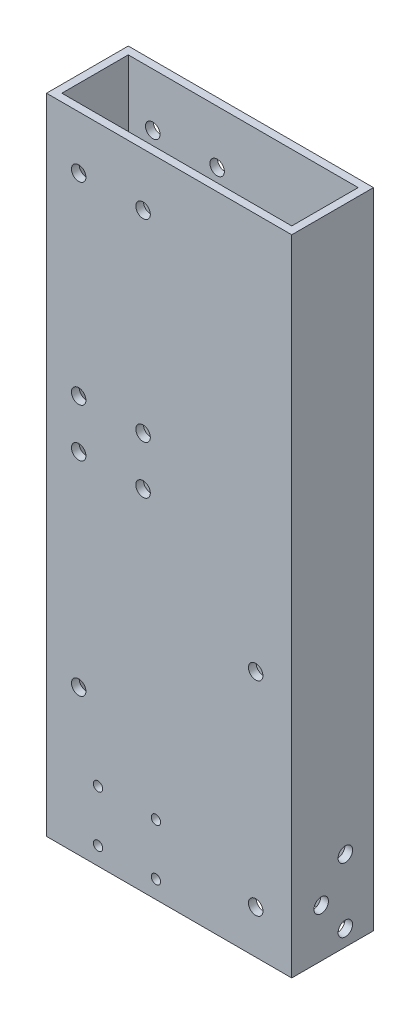
SolidWorks part; units mm, degrees
material "6061-T6 (SS)"
ref_plane "Front Plane" through (0, 0, 0) normal (0, 0, 1) x (1, 0, 0)
ref_plane "Top Plane" through (0, 0, 0) normal (0, 1, 0) x (1, 0, 0)
ref_plane "Right Plane" through (0, 0, 0) normal (1, 0, 0) x (0, 0, -1)
sketch "Sketch1" plane through (0, 0, 0) normal (0, 1, 0) x (1, 0, 0)
  line L1 (-76.2, 25.4) -> (76.2, 25.4)
  line L2 (-76.2, 25.4) -> (-76.2, -25.4)
  line L3 (-76.2, -25.4) -> (76.2, -25.4)
  line L4 (76.2, 25.4) -> (76.2, -25.4)
  line L5 (-76.2, 25.4) -> (76.2, -25.4) construction
  line L6 (-76.2, -25.4) -> (76.2, 25.4) construction
  point P0 (0, 0)
  dimension "D1" = 152.4
  dimension "D2" = 50.8
extrude "Extrude-Thin1" add sketch "Sketch1" along normal blind 400 thin
hole_wizard "M8 Clearance Hole1" positions "Sketch3" profile "Sketch4" hole size "M8" standard "ANSI Metric" end condition through all
sketch "Sketch3" plane through (0, 0, 25.4) normal (0, 0, 1) x (1, 0, 0)
  line L0 (-76.2, 227) -> (3.8, 227)
  line L1 (-76.2, 400) -> (-76.2, 0) construction
  line L3 (-76.2, 0) -> (76.2, 0) construction
  line L4 (3.8, 227) -> (3.8, 387)
  line L5 (3.8, 387) -> (-76.2, 387)
  line L6 (-76.2, 387) -> (-76.2, 227)
  line L8 (-56.2, 217) -> (-16.2, 217)
  line L11 (-56.2, 217) -> (-56.2, 153.6667)
  line L12 (-56.2, 153.6667) -> (-56.2, 90.3333)
  line L13 (-56.2, 90.3333) -> (-56.2, 27)
  line L15 (-36.2, 217) -> (-36.2, 227)
  line L17 (-56.2, 27) -> (53.8, 27)
  line L18 (53.8, 27) -> (53.8, 153.6667)
  line L19 (53.8, 153.6667) -> (-56.2, 153.6667)
  line L22 (-56.2, 90.3333) -> (-76.2, 90.3333)
  line L27 (-36.2, 425) -> (-36.2, 387)
  circle A0 centre (-36.2, 425) radius 49.2125
  point P18 (-56.2, 217)
  point P19 (-16.2, 217)
  point P26 (-56.2, 90.3333)
  point P35 (53.8, 27)
  point P36 (53.8, 153.6667)
  dimension "D9" = 98.425
  dimension "D1" = 200
  dimension "D2" = 80
  dimension "D3" = 160
  dimension "D4" = 27
  dimension "D5" = 10
  dimension "D6" = 40
  dimension "D7" = 110
  dimension "D8" = 38
sketch "Sketch4" plane through (53.8, 153.6667, 25.4) normal (1, 0, 0) x (0, -1, 0)
  line L0 (0, 0) -> (0, 50.8)
  line L1 (0, 50.8) -> (4.5, 50.8)
  line L2 (4.5, 50.8) -> (4.5, 0)
  line L5 (4.5, 0) -> (0, 0)
  line L11 (0, -6.35) -> (0, 107.95) construction
  dimension "Thru Hole Dia." = 9
  dimension "Thru Hole Depth" = 50.8
hole_wizard "M8 Clearance Hole2" positions "Sketch5" profile "Sketch6" hole size "M8" standard "ANSI Metric" end condition through all
sketch "Sketch5" plane through (0, 0, 25.4) normal (0, 0, 1) x (1, 0, 0)
  line L1 (-56.2, 367) -> (-16.2, 367)
  line L2 (-56.2, 367) -> (-56.2, 247)
  line L3 (-56.2, 247) -> (-16.2, 247)
  line L4 (-16.2, 367) -> (-16.2, 247)
  line L5 (-56.2, 217) -> (-16.2, 217) construction
  line L6 (-36.2, 227) -> (-36.2, 247)
  line L7 (-76.2, 227) -> (3.8, 227) construction
  point P1 (-56.2, 367)
  point P2 (-16.2, 247)
  point P153 (-56.2, 247)
  point P154 (-16.2, 367)
  dimension "D1" = 20
  dimension "D2" = 120
sketch "Sketch6" plane through (-56.2, 367, 25.4) normal (1, 0, 0) x (0, -1, 0)
  line L0 (0, 0) -> (0, 50.8)
  line L1 (0, 50.8) -> (4.5, 50.8)
  line L2 (4.5, 50.8) -> (4.5, 0)
  line L5 (4.5, 0) -> (0, 0)
  line L11 (0, -6.35) -> (0, 107.95) construction
  dimension "Thru Hole Dia." = 9
  dimension "Thru Hole Depth" = 50.8
hole_wizard "M5 Clearance Hole1" positions "Sketch10" profile "Sketch11" hole size "M5" standard "ANSI Metric" end condition through all
sketch "Sketch10" plane through (0, 0, 25.4) normal (0, 0, 1) x (1, 0, 0)
  line L1 (-8.2, 43) -> (-44.2, 43)
  line L2 (-8.2, 43) -> (-8.2, 11)
  line L3 (-8.2, 11) -> (-44.2, 11)
  line L4 (-44.2, 43) -> (-44.2, 11)
  line L5 (-8.2, 43) -> (-44.2, 11) construction
  line L6 (-8.2, 11) -> (-44.2, 43) construction
  line L8 (-56.2, 27) -> (53.8, 27) construction
  line L9 (-76.2, 400) -> (-76.2, 0) construction
  point P2 (-44.2, 11)
  point P107 (-8.2, 43)
  point P108 (-8.2, 11)
  point P109 (-44.2, 43)
  point P114 (-26.2, 27)
  dimension "D1" = 36
  dimension "D2" = 32
  dimension "D3" = 50
sketch "Sketch11" plane through (-44.2, 11, 25.4) normal (1, 0, 0) x (0, -1, 0)
  line L0 (0, 0) -> (0, 50.8)
  line L1 (0, 50.8) -> (2.9, 50.8)
  line L2 (2.9, 50.8) -> (2.9, 0)
  line L5 (2.9, 0) -> (0, 0)
  line L11 (0, -6.35) -> (0, 107.95) construction
  dimension "Thru Hole Dia." = 5.8
  dimension "Thru Hole Depth" = 50.8
hole_wizard "M8 Clearance Hole3" positions "Sketch12" profile "Sketch14" hole size "M8" standard "ANSI Metric"
sketch "Sketch12" plane through (76.2, 0, 0) normal (1, 0, 0) x (0, 0, -1)
  line L1 (-7.9, 50) -> (7.1, 50)
  line L2 (-7.9, 50) -> (-7.9, 10)
  line L3 (-7.9, 10) -> (7.1, 10)
  line L4 (7.1, 50) -> (7.1, 10)
  line L5 (-25.4, 0) -> (25.4, 0) construction
  line L6 (-25.4, 90.3333) -> (-25.4, 27) construction
  point P1 (-7.9, 50)
  point P87 (-7.9, 10)
  point P98 (7.1, 30)
  dimension "D1" = 10
  dimension "D2" = 17.5
  dimension "D3" = 15
  dimension "D4" = 40
sketch "Sketch14" plane through (76.2, 50, 7.9) normal (0, 1, 0) x (0, 0, -1)
  line L0 (0, 0) -> (0, 4.7625)
  line L1 (0, 4.7625) -> (4.5, 4.7625)
  line L2 (4.5, 4.7625) -> (4.5, 0)
  line L5 (4.5, 0) -> (0, 0)
  line L11 (0, -6.35) -> (0, 107.95) construction
  dimension "Thru Hole Dia." = 9
  dimension "Thru Hole Depth" = 4.7625
hole_wizard "Ø20.0 (20) Diameter Hole1" positions "Sketch15" profile "Sketch16" hole size "Ø20.0" standard "ANSI Metric"
sketch "Sketch15" plane through (-76.2, 0, 0) normal (-1, 0, 0) x (0, 0, 1)
  line L0 (7.9, 50) -> (-7.1, 30)
  point P0 (0.4, 40)
sketch "Sketch16" plane through (-76.2, 40, 0.4) normal (0, 1, 0) x (0, 0, 1)
  line L0 (0, 0) -> (0, 4.7625)
  line L1 (0, 4.7625) -> (10, 4.7625)
  line L2 (10, 4.7625) -> (10, 0)
  line L5 (10, 0) -> (0, 0)
  line L11 (0, -6.35) -> (0, 107.95) construction
  dimension "Thru Hole Dia." = 20
  dimension "Thru Hole Depth" = 4.7625
sketch "Sketch9" [suppressed] plane through (0, 0, 0) normal (0, 0, 1) x (1, 0, 0)
  circle A0 centre (-36.2, 425) radius 22.225
  dimension "D1" = 44.45
extrude "Cut-Extrude1" [suppressed] cut sketch "Sketch9" against normal through all and the other way through all
hole_wizard "Ø12.0 (12) Diameter Hole1" [suppressed] positions "Sketch7" profile "Sketch8" hole size "Ø12.0" standard "ANSI Metric"
sketch "Sketch7" [suppressed] plane through (0, 0, -25.4) normal (0, 0, -1) x (-1, 0, 0)
  line L0 (-13.0125, 425) -> (36.2, 375.7875)
  line L3 (-13.0125, 425) -> (36.2, 474.2125)
  line L4 (36.2, 474.2125) -> (85.4125, 425)
  line L5 (85.4125, 425) -> (36.2, 375.7875)
  line L7 (36.2, 425) -> (36.2, 387) construction
  circle A0 centre (36.2, 425) radius 49.2125 construction
  point P0 (36.2, 375.7875)
  point P4 (-13.0125, 425)
  point P6 (36.2, 474.2125)
sketch "Sketch8" [suppressed] plane through (-36.2, 375.7875, -25.4) normal (1, 0, 0) x (0, 1, 0)
  line L0 (0, 0) -> (0, 4.7625)
  line L1 (0, 4.7625) -> (6, 4.7625)
  line L2 (6, 4.7625) -> (6, 0)
  line L5 (6, 0) -> (0, 0)
  line L11 (0, -6.35) -> (0, 107.95) construction
  dimension "Thru Hole Dia." = 12
  dimension "Thru Hole Depth" = 4.7625
mirror "Mirror1" about plane through (0, 0, 0) normal (0, 0, 1) of bodies 108
delete or keep bodies "Body-Delete/Keep 1" type delete bodies bodies 108
